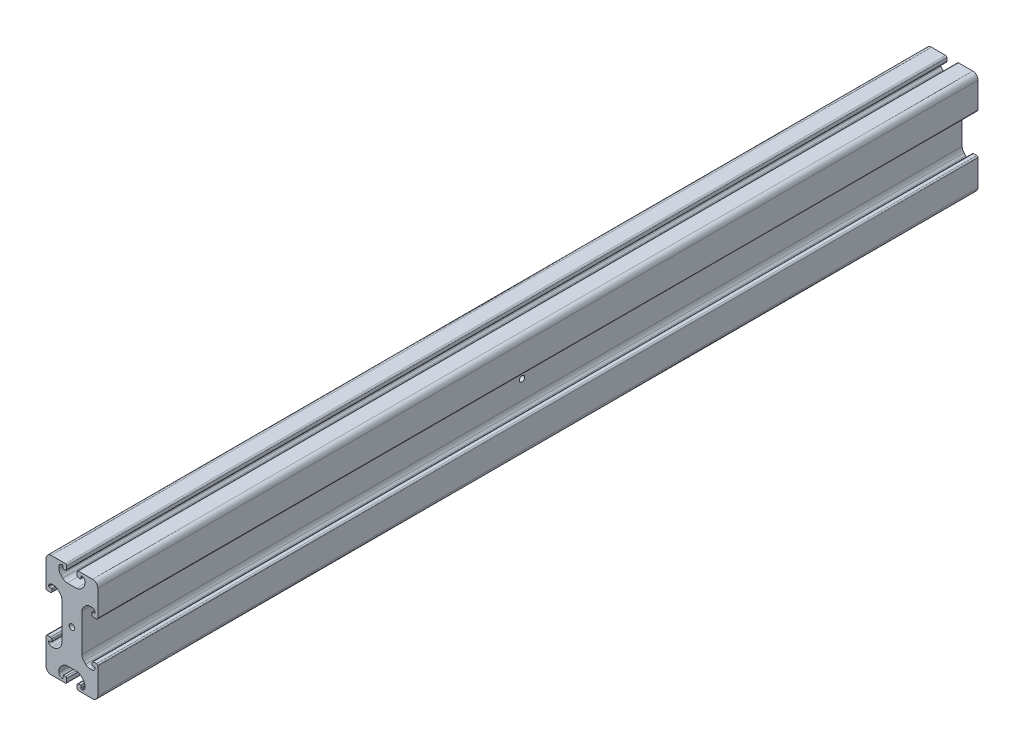
SolidWorks part; units mm, degrees
material "氧化铝"
ref_plane "前视基准面" through (0, 0, 0) normal (0, 0, 1) x (1, 0, 0)
ref_plane "上视基准面" through (0, 0, 0) normal (0, 1, 0) x (1, 0, 0)
ref_plane "右视基准面" through (0, 0, 0) normal (1, 0, 0) x (0, 0, -1)
sketch "Model" plane through (0, 0, 0) normal (0, 0, 1) x (1, 0, 0)
  line L64 (3.9995, -39.0002) -> (3.9995, -36.5001)
  line L65 (10.6569, -19.4779) -> (9.2144, -18.0355)
  line L66 (15.4999, -20.9425) -> (14.1924, -20.9425)
  line L67 (16.0001, -17.9425) -> (17.55, -17.9425)
  line L68 (17.9999, -18.3924) -> (17.9999, -18.4425)
  line L69 (15.4999, -15.9424) -> (15.4999, -17.4426)
  line L70 (18.9998, -14.9425) -> (16.5, -14.9425)
  line L71 (-3.5582, -27.7502) -> (3.557, -27.7502)
  line L72 (19.9995, -36) -> (20, -15.9424)
  line L73 (6.9995, -37.5501) -> (6.9995, -36.0002)
  line L74 (4.9994, -35.5002) -> (6.4995, -35.5002)
  line L75 (7.4494, -38.0003) -> (7.4995, -38.0003)
  line L76 (8.5349, -30.6572) -> (7.0927, -29.2148)
  line L77 (9.9995, -35.5002) -> (9.9995, -34.1927)
  line L78 (4.9994, -40.0002) -> (15.9996, -40.0003)
  line L79 (-5.0006, -40.0002) -> (-16.0007, -40.0003)
  line L80 (-10.0007, -35.5002) -> (-10.0007, -34.1927)
  line L81 (-8.5361, -30.6572) -> (-7.0939, -29.2148)
  line L82 (-7.4506, -38.0003) -> (-7.5006, -38.0003)
  line L83 (-5.0006, -35.5002) -> (-6.5007, -35.5002)
  line L84 (-7.0007, -37.5501) -> (-7.0007, -36.0002)
  line L85 (-20.0007, -36) -> (-20.0006, -15.9424)
  line L86 (-19.0004, -14.9425) -> (-16.5006, -14.9425)
  line L87 (-15.5004, -15.9424) -> (-15.5004, -17.4426)
  line L88 (-18.0005, -18.3924) -> (-18.0005, -18.4425)
  line L89 (-16.0006, -17.9425) -> (-17.5506, -17.9425)
  line L90 (-15.5004, -20.9425) -> (-14.193, -20.9425)
  line L91 (-10.6575, -19.4779) -> (-9.215, -18.0355)
  line L92 (-4.0007, -39.0002) -> (-4.0007, -36.5001)
  line L110 (-7.7503, 14.5) -> (-7.7507, -14.5)
  line L111 (7.7501, 14.5) -> (7.7501, -14.5)
  line L122 (-3.9998, 39.0001) -> (-3.9999, 36.5)
  line L123 (-10.657, 19.478) -> (-9.2146, 18.0355)
  line L124 (-15.5, 20.9427) -> (-14.1925, 20.9427)
  line L125 (-16.0003, 17.9427) -> (-17.5502, 17.9427)
  line L126 (-18.0001, 18.3926) -> (-18.0001, 18.4427)
  line L127 (-15.5001, 15.9426) -> (-15.5001, 17.4427)
  line L128 (-19.0001, 14.9427) -> (-16.5003, 14.9427)
  line L129 (-19.9999, 36.0003) -> (-20.0003, 15.9427)
  line L130 (-6.9999, 37.5501) -> (-6.9999, 36.0001)
  line L131 (-4.9998, 35.5001) -> (-6.5, 35.5002)
  line L132 (-7.4498, 38.0002) -> (-7.4998, 38.0002)
  line L133 (-8.5354, 30.6572) -> (-7.0933, 29.2148)
  line L134 (-9.9999, 35.5002) -> (-10, 34.1928)
  line L135 (-4.9997, 40.0002) -> (-15.9999, 40.0005)
  line L136 (5.0003, 40) -> (16.0004, 39.9998)
  line L137 (10.0003, 35.4998) -> (10.0002, 34.1923)
  line L138 (8.5356, 30.6569) -> (7.0933, 29.2144)
  line L139 (7.4502, 37.9999) -> (7.5003, 37.9999)
  line L140 (5.0002, 35.4999) -> (6.5003, 35.4999)
  line L141 (7.0003, 37.5498) -> (7.0003, 35.9998)
  line L142 (20.0003, 35.9994) -> (20, 15.9422)
  line L143 (-3.5576, 27.7501) -> (3.5576, 27.7499)
  line L144 (18.9999, 14.9423) -> (16.5, 14.9423)
  line L145 (15.4999, 15.9423) -> (15.4999, 17.4424)
  line L146 (18, 18.3922) -> (18, 18.4423)
  line L147 (16.0001, 17.9423) -> (17.5501, 17.9423)
  line L148 (15.5, 20.9424) -> (14.1925, 20.9424)
  line L149 (10.657, 19.4779) -> (9.2145, 18.0355)
  line L150 (4.0003, 38.9999) -> (4.0003, 36.4999)
  spline S0 degree 3 poles (4.9994, -40.0002) (4.783, -40.0002) (4.2843, -39.7825) (3.9995, -39.3559) (3.9995, -39.0002) knots 0 0 0 0 0.421034 1 1 1 1
  spline S1 degree 3 poles (9.2144, -18.0355) (8.7501, -17.5712) (8.0561, -16.4792) (7.7501, -15.1965) (7.7501, -14.5) knots 0 0 0 0 0.481772 1 1 1 1
  spline S2 degree 3 poles (14.1924, -20.9425) (13.5137, -20.9425) (12.2458, -20.6698) (11.1406, -19.9617) (10.6569, -19.4779) knots 0 0 0 0 0.495307 1 1 1 1
  spline S3 degree 3 poles (17.9999, -18.4425) (17.9999, -19.2744) (17.35, -20.3704) (16.1019, -20.9425) (15.4999, -20.9425) knots 0 0 0 0 0.543506 1 1 1 1
  spline S4 degree 3 poles (17.55, -17.9425) (17.7169, -17.9425) (17.9057, -18.0771) (17.9999, -18.3012) (17.9999, -18.3924) knots 0 0 0 0 0.601272 1 1 1 1
  spline S5 degree 3 poles (15.4999, -17.4426) (15.4999, -17.6087) (15.6299, -17.8279) (15.8796, -17.9425) (16.0001, -17.9425) knots 0 0 0 0 0.543008 1 1 1 1
  spline S6 degree 3 poles (16.5, -14.9425) (16.1641, -14.9425) (15.7274, -15.206) (15.4999, -15.7052) (15.4999, -15.9424) knots 0 0 0 0 0.548464 1 1 1 1
  spline S7 degree 3 poles (20, -15.9424) (20, -15.6052) (19.7349, -15.1692) (19.2356, -14.9425) (18.9998, -14.9425) knots 0 0 0 0 0.550415 1 1 1 1
  spline S8 degree 3 poles (7.4995, -38.0003) (8.1967, -38.0003) (9.4396, -37.3965) (9.9995, -36.2593) (9.9995, -35.5002) knots 0 0 0 0 0.502794 1 1 1 1
  spline S9 degree 3 poles (6.9995, -37.5501) (6.9995, -37.6839) (7.1264, -37.9051) (7.3299, -38.0003) (7.4494, -38.0003) knots 0 0 0 0 0.549542 1 1 1 1
  spline S10 degree 3 poles (6.4995, -35.5002) (6.6304, -35.5002) (6.8797, -35.6177) (6.9995, -35.8418) (6.9995, -36.0002) knots 0 0 0 0 0.482406 1 1 1 1
  spline S11 degree 3 poles (3.9995, -36.5001) (3.9995, -36.1962) (4.2934, -35.7061) (4.7456, -35.5002) (4.9994, -35.5002) knots 0 0 0 0 0.565195 1 1 1 1
  spline S12 degree 3 poles (7.0927, -29.2148) (6.6266, -28.7485) (5.5204, -28.0389) (4.2569, -27.7502) (3.557, -27.7502) knots 0 0 0 0 0.489373 1 1 1 1
  spline S13 degree 3 poles (9.9995, -34.1927) (9.9995, -33.5034) (9.7081, -32.2212) (9.0084, -31.1307) (8.5349, -30.6572) knots 0 0 0 0 0.510204 1 1 1 1
  spline S14 degree 3 poles (15.9996, -40.0003) (17.3485, -40.0003) (19.0923, -38.9397) (19.9995, -36.9427) (19.9995, -36) knots 0 0 0 0 0.550548 1 1 1 1
  spline S45 degree 3 poles (-16.0007, -40.0003) (-17.3497, -40.0003) (-19.0935, -38.9397) (-20.0007, -36.9427) (-20.0007, -36) knots 0 0 0 0 0.550548 1 1 1 1
  spline S46 degree 3 poles (-10.0007, -34.1927) (-10.0007, -33.5034) (-9.7093, -32.2212) (-9.0096, -31.1307) (-8.5361, -30.6572) knots 0 0 0 0 0.510204 1 1 1 1
  spline S47 degree 3 poles (-7.0939, -29.2148) (-6.6277, -28.7485) (-5.5216, -28.0389) (-4.2581, -27.7502) (-3.5582, -27.7502) knots 0 0 0 0 0.489373 1 1 1 1
  spline S48 degree 3 poles (-4.0007, -36.5001) (-4.0007, -36.1962) (-4.2946, -35.7061) (-4.7468, -35.5002) (-5.0006, -35.5002) knots 0 0 0 0 0.565195 1 1 1 1
  spline S49 degree 3 poles (-6.5007, -35.5002) (-6.6316, -35.5002) (-6.8809, -35.6177) (-7.0007, -35.8418) (-7.0007, -36.0002) knots 0 0 0 0 0.482406 1 1 1 1
  spline S50 degree 3 poles (-7.0007, -37.5501) (-7.0007, -37.6839) (-7.1276, -37.9051) (-7.3311, -38.0003) (-7.4506, -38.0003) knots 0 0 0 0 0.549542 1 1 1 1
  spline S51 degree 3 poles (-7.5006, -38.0003) (-8.1979, -38.0003) (-9.4408, -37.3965) (-10.0007, -36.2593) (-10.0007, -35.5002) knots 0 0 0 0 0.502794 1 1 1 1
  spline S52 degree 3 poles (-20.0006, -15.9424) (-20.0006, -15.6052) (-19.7355, -15.1692) (-19.2362, -14.9425) (-19.0004, -14.9425) knots 0 0 0 0 0.550415 1 1 1 1
  spline S53 degree 3 poles (-16.5006, -14.9425) (-16.1647, -14.9425) (-15.728, -15.206) (-15.5004, -15.7052) (-15.5004, -15.9424) knots 0 0 0 0 0.548464 1 1 1 1
  spline S54 degree 3 poles (-15.5004, -17.4426) (-15.5004, -17.6087) (-15.6305, -17.8279) (-15.8802, -17.9425) (-16.0006, -17.9425) knots 0 0 0 0 0.543008 1 1 1 1
  spline S55 degree 3 poles (-17.5506, -17.9425) (-17.7175, -17.9425) (-17.9063, -18.0771) (-18.0005, -18.3012) (-18.0005, -18.3924) knots 0 0 0 0 0.601272 1 1 1 1
  spline S56 degree 3 poles (-18.0005, -18.4425) (-18.0005, -19.2744) (-17.3506, -20.3704) (-16.1024, -20.9425) (-15.5004, -20.9425) knots 0 0 0 0 0.543506 1 1 1 1
  spline S57 degree 3 poles (-14.193, -20.9425) (-13.5143, -20.9425) (-12.2464, -20.6698) (-11.1412, -19.9617) (-10.6575, -19.4779) knots 0 0 0 0 0.495307 1 1 1 1
  spline S58 degree 3 poles (-9.215, -18.0355) (-8.7507, -17.5712) (-8.0567, -16.4792) (-7.7507, -15.1965) (-7.7507, -14.5) knots 0 0 0 0 0.481772 1 1 1 1
  spline S59 degree 3 poles (-5.0006, -40.0002) (-4.7842, -40.0002) (-4.2854, -39.7825) (-4.0007, -39.3559) (-4.0007, -39.0002) knots 0 0 0 0 0.421034 1 1 1 1
  spline S64 degree 3 poles (-4.9997, 40.0002) (-4.7833, 40.0002) (-4.2846, 39.7824) (-3.9998, 39.3558) (-3.9998, 39.0001) knots 0 0 0 0 0.421034 1 1 1 1
  spline S65 degree 3 poles (-9.2146, 18.0355) (-8.7503, 17.5712) (-8.0564, 16.4792) (-7.7503, 15.1965) (-7.7503, 14.5) knots 0 0 0 0 0.481772 1 1 1 1
  spline S66 degree 3 poles (-14.1925, 20.9427) (-13.5139, 20.9427) (-12.246, 20.6699) (-11.1407, 19.9617) (-10.657, 19.478) knots 0 0 0 0 0.495307 1 1 1 1
  spline S67 degree 3 poles (-18.0001, 18.4427) (-18.0001, 19.2746) (-17.3502, 20.3706) (-16.102, 20.9427) (-15.5, 20.9427) knots 0 0 0 0 0.543506 1 1 1 1
  spline S68 degree 3 poles (-17.5502, 17.9427) (-17.7171, 17.9427) (-17.9059, 18.0773) (-18.0001, 18.3015) (-18.0001, 18.3926) knots 0 0 0 0 0.601272 1 1 1 1
  spline S69 degree 3 poles (-15.5001, 17.4427) (-15.5001, 17.6089) (-15.6301, 17.828) (-15.8798, 17.9427) (-16.0003, 17.9427) knots 0 0 0 0 0.543008 1 1 1 1
  spline S70 degree 3 poles (-16.5003, 14.9427) (-16.1644, 14.9427) (-15.7277, 15.2062) (-15.5001, 15.7054) (-15.5001, 15.9426) knots 0 0 0 0 0.548464 1 1 1 1
  spline S71 degree 3 poles (-20.0003, 15.9427) (-20.0003, 15.6055) (-19.7352, 15.1695) (-19.2359, 14.9428) (-19.0001, 14.9427) knots 0 0 0 0 0.550415 1 1 1 1
  spline S72 degree 3 poles (-7.4998, 38.0002) (-8.1971, 38.0003) (-9.44, 37.3965) (-9.9999, 36.2594) (-9.9999, 35.5002) knots 0 0 0 0 0.502794 1 1 1 1
  spline S73 degree 3 poles (-6.9999, 37.5501) (-6.9999, 37.6839) (-7.1268, 37.9051) (-7.3303, 38.0002) (-7.4498, 38.0002) knots 0 0 0 0 0.549542 1 1 1 1
  spline S74 degree 3 poles (-6.5, 35.5002) (-6.6308, 35.5002) (-6.8802, 35.6177) (-6.9999, 35.8418) (-6.9999, 36.0001) knots 0 0 0 0 0.482406 1 1 1 1
  spline S75 degree 3 poles (-3.9999, 36.5) (-3.9999, 36.1962) (-4.2938, 35.7061) (-4.7461, 35.5001) (-4.9998, 35.5001) knots 0 0 0 0 0.565195 1 1 1 1
  spline S76 degree 3 poles (-7.0933, 29.2148) (-6.6271, 28.7485) (-5.521, 28.0389) (-4.2575, 27.7501) (-3.5576, 27.7501) knots 0 0 0 0 0.489373 1 1 1 1
  spline S77 degree 3 poles (-10, 34.1928) (-10, 33.5035) (-9.7086, 32.2212) (-9.0089, 31.1308) (-8.5354, 30.6572) knots 0 0 0 0 0.510204 1 1 1 1
  spline S78 degree 3 poles (-15.9999, 40.0005) (-17.3488, 40.0005) (-19.0926, 38.9399) (-19.9999, 36.9429) (-19.9999, 36.0003) knots 0 0 0 0 0.550548 1 1 1 1
  spline S105 degree 3 poles (16.0004, 39.9998) (17.3494, 39.9998) (19.0931, 38.9391) (20.0003, 36.9421) (20.0003, 35.9994) knots 0 0 0 0 0.550548 1 1 1 1
  spline S106 degree 3 poles (10.0002, 34.1923) (10.0002, 33.5031) (9.7088, 32.2208) (9.009, 31.1304) (8.5356, 30.6569) knots 0 0 0 0 0.510204 1 1 1 1
  spline S107 degree 3 poles (7.0933, 29.2144) (6.6272, 28.7482) (5.521, 28.0386) (4.2575, 27.7499) (3.5576, 27.7499) knots 0 0 0 0 0.489373 1 1 1 1
  spline S108 degree 3 poles (4.0003, 36.4999) (4.0002, 36.196) (4.2942, 35.7059) (4.7464, 35.4999) (5.0002, 35.4999) knots 0 0 0 0 0.565195 1 1 1 1
  spline S109 degree 3 poles (6.5003, 35.4999) (6.6311, 35.4999) (6.8805, 35.6174) (7.0003, 35.8415) (7.0003, 35.9998) knots 0 0 0 0 0.482406 1 1 1 1
  spline S110 degree 3 poles (7.0003, 37.5498) (7.0003, 37.6836) (7.1272, 37.9048) (7.3307, 37.9999) (7.4502, 37.9999) knots 0 0 0 0 0.549542 1 1 1 1
  spline S111 degree 3 poles (7.5003, 37.9999) (8.1975, 37.9999) (9.4404, 37.3961) (10.0003, 36.259) (10.0003, 35.4998) knots 0 0 0 0 0.502794 1 1 1 1
  spline S112 degree 3 poles (20, 15.9422) (20, 15.605) (19.735, 15.169) (19.2356, 14.9423) (18.9999, 14.9423) knots 0 0 0 0 0.550415 1 1 1 1
  spline S113 degree 3 poles (16.5, 14.9423) (16.1641, 14.9423) (15.7274, 15.2059) (15.4999, 15.7051) (15.4999, 15.9423) knots 0 0 0 0 0.548464 1 1 1 1
  spline S114 degree 3 poles (15.4999, 17.4424) (15.4999, 17.6085) (15.63, 17.8277) (15.8797, 17.9424) (16.0001, 17.9423) knots 0 0 0 0 0.543008 1 1 1 1
  spline S115 degree 3 poles (17.5501, 17.9423) (17.717, 17.9423) (17.9058, 18.0769) (18, 18.301) (18, 18.3922) knots 0 0 0 0 0.601272 1 1 1 1
  spline S116 degree 3 poles (18, 18.4423) (18, 19.2741) (17.3502, 20.3702) (16.102, 20.9424) (15.5, 20.9424) knots 0 0 0 0 0.543506 1 1 1 1
  spline S117 degree 3 poles (14.1925, 20.9424) (13.5139, 20.9424) (12.246, 20.6697) (11.1407, 19.9616) (10.657, 19.4779) knots 0 0 0 0 0.495307 1 1 1 1
  spline S118 degree 3 poles (9.2145, 18.0355) (8.7502, 17.5712) (8.0562, 16.4792) (7.7501, 15.1965) (7.7501, 14.5) knots 0 0 0 0 0.481772 1 1 1 1
  spline S119 degree 3 poles (5.0003, 40) (4.7839, 40) (4.2851, 39.7822) (4.0003, 39.3557) (4.0003, 38.9999) knots 0 0 0 0 0.421034 1 1 1 1
  point P4 (-7.7505, 0)
  point P53 (-7.7505, 0)
  point P56 (7.7501, 0)
extrude "凸台-拉伸3" add sketch "Model" along normal blind 680 contours S1 L111 S118 L149 S117 L148 S116 L146 S115 L147 S114 L145 S113 L144 S112 L142 S105 L136 S119 L150 S108 L140 S109 L141 S110 L139 S111 L137 S106 L138 S107 L143 S76 L133 S77 L134 S72 L132 S73 L130 S74 L131 S75 L122 S64 L135 S78 L129 S71 L128 S70 L127 S69 L125 S68 L126 S67 L124 S66 L123 S65 L110 S58 L91 S57 L90 S56 L88 S55 L89 S54 L87 S53 L86 S52 L85 S45 L79 S59 L92 S48 L83 S49 L84 S50 L82 S51 L80 S46 L81 S47 L71 S12 L76 S13 L77 S8 L75 S9 L73 S10 L74 S11 L64 S0 L78 S14 L72 S7 L70 S6 L69 S5 L67 S4 L68 S3 L66 S2 L65
sketch "草图11" plane through (0, 0, 0) normal (0, 0, -1) x (-1, 0, 0)
  line L2 (5.0006, -40.0002) -> (16.0007, -40.0003) construction
  point P0 (0, -0.0002)
  dimension "D1" = 40
hole_wizard "M5 螺纹孔3" positions "草图12" profile "草图13" tap size "M5" standard "GB" end condition through all
sketch "草图12" plane through (0, 0, 0) normal (0, 0, -1) x (-1, 0, 0)
  point P0 (0, 0)
sketch "草图13" plane through (0, 0, 0) normal (1, 0, 0) x (0, 1, 0)
  line L0 (0, 0) -> (0, 680)
  line L1 (0, 680) -> (2.1, 680)
  line L2 (2.1, 680) -> (2.1, 0)
  line L5 (2.1, 0) -> (0, 0)
  line L11 (0, -6.35) -> (0, 107.95) construction
  dimension "通孔螺纹孔钻头直径" = 4.2
  dimension "通孔螺纹孔钻头深度" = 680
cosmetic thread "孔螺蚊线3" parameters "D2"=5
ref_plane "基准面5" through (0, -40, 0) normal (0, 1, 0) x (1, 0, 0)
ref_plane "基准面6" through (0, 40, 0) normal (0, 1, 0) x (1, 0, 0)
sketch "草图14" plane through (-7.7505, 0.0001, 0) normal (-1, 0, 0) x (0, 0, 1)
  line L0 (0, 14.4999) -> (0, -14.5001) construction
  point P0 (340, 0)
  dimension "D1" = 340
hole_wizard "M5 螺纹孔4" positions "草图15" profile "草图16" tap size "M5" standard "GB" end condition through all
sketch "草图15" plane through (-7.7505, 0.0001, 0) normal (-1, 0, 0) x (0, 0, 1)
  point P0 (340, 0)
sketch "草图16" plane through (-7.7505, 0.0001, 340) normal (0, 0, 1) x (0, -1, 0)
  line L0 (0, 0) -> (0, 27.7512)
  line L1 (0, 27.7512) -> (2.1, 27.7512)
  line L2 (2.1, 27.7512) -> (2.1, 0)
  line L5 (2.1, 0) -> (0, 0)
  line L11 (0, -6.35) -> (0, 107.95) construction
  dimension "通孔螺纹孔钻头直径" = 4.2
  dimension "通孔螺纹孔钻头深度" = 27.7512
cosmetic thread "孔螺蚊线4" parameters "D2"=5
